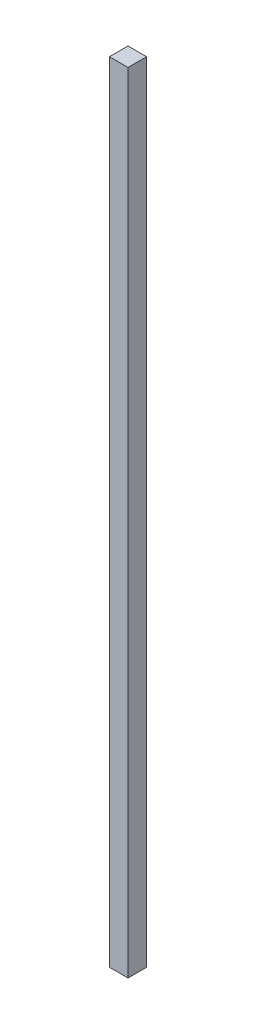
SolidWorks part; units mm, degrees
ref_plane "Front Plane" through (0, 0, 0) normal (0, 0, 1) x (1, 0, 0)
ref_plane "Top Plane" through (0, 0, 0) normal (0, 1, 0) x (1, 0, 0)
ref_plane "Right Plane" through (0, 0, 0) normal (1, 0, 0) x (0, 0, -1)
other "Configuration Table"
sketch "Sketch1" plane through (0, 0, 0) normal (0, 0, 1) x (1, 0, 0)
  line L1 (126, 640) -> (134, 640)
  line L2 (126, 640) -> (126, 980)
  line L3 (126, 980) -> (134, 980)
  line L4 (134, 640) -> (134, 980)
extrude "PACK_kapak_kolu_dikey_1_1" add sketch "Sketch1" against normal blind 8 from offset 596 separate body
